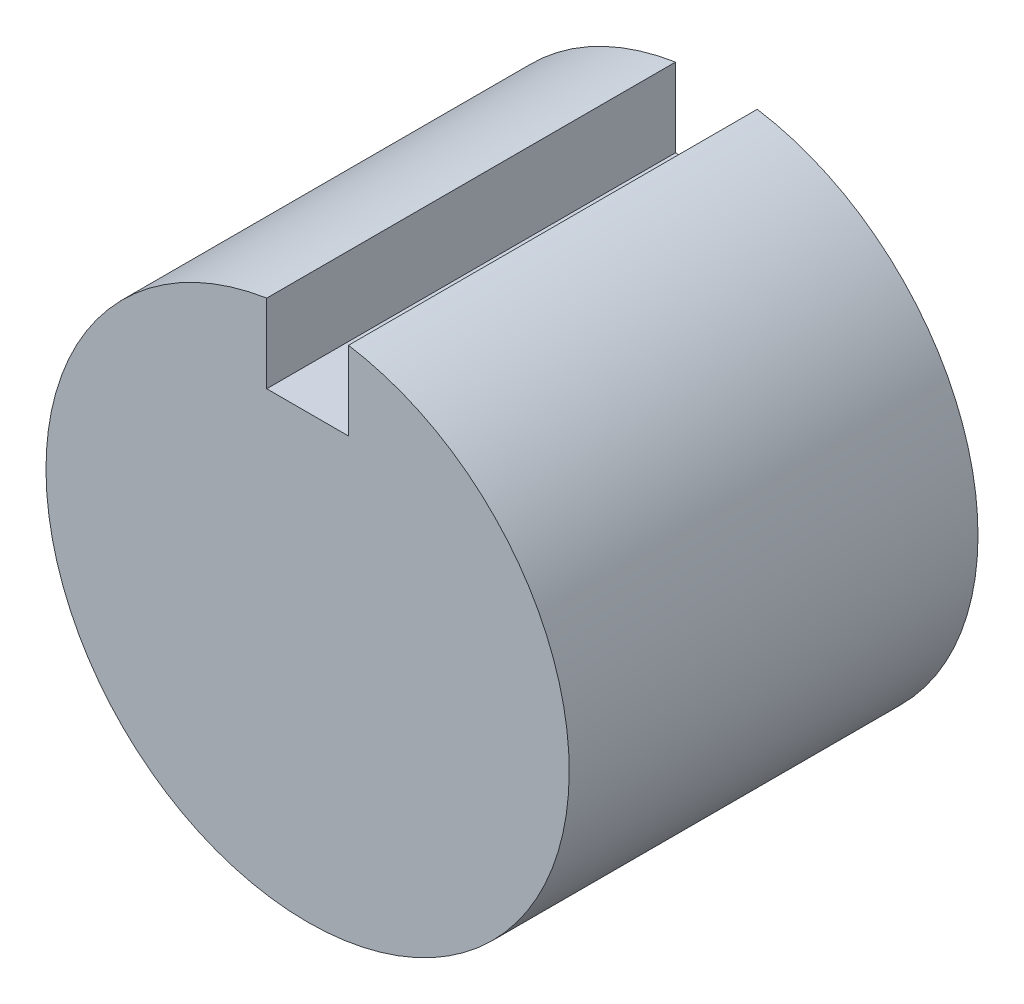
SolidWorks part; units mm, degrees
ref_plane "Ön Düzlem" through (0, 0, 0) normal (0, 0, 1) x (1, 0, 0)
ref_plane "Üst Düzlem" through (0, 0, 0) normal (0, 1, 0) x (1, 0, 0)
ref_plane "Sağ Düzlem" through (0, 0, 0) normal (1, 0, 0) x (0, 0, -1)
sketch "Çizim1" plane through (0, 0, 0) normal (0, 0, 1) x (1, 0, 0)
  circle A0 centre (0, 0) radius 6.4
extrude "Yükseklik-Ekstrüzyon1" add sketch "Çizim1" along normal blind 10
sketch "Çizim2" plane through (0, 0, 0) normal (0, 0, -1) x (-1, 0, 0)
  line L1 (1, 4.4) -> (-1, 4.4)
  line L2 (-1, 4.4) -> (-1, 6.3214)
  line L3 (1, 4.4) -> (1, 6.3214)
  circle A0 centre (0, 0) radius 6.4 construction
  point P9 (0, 4.4)
extrude "Kes-Ekstrüzyon1" cut sketch "Çizim2" against normal blind 10 and the other way through all
